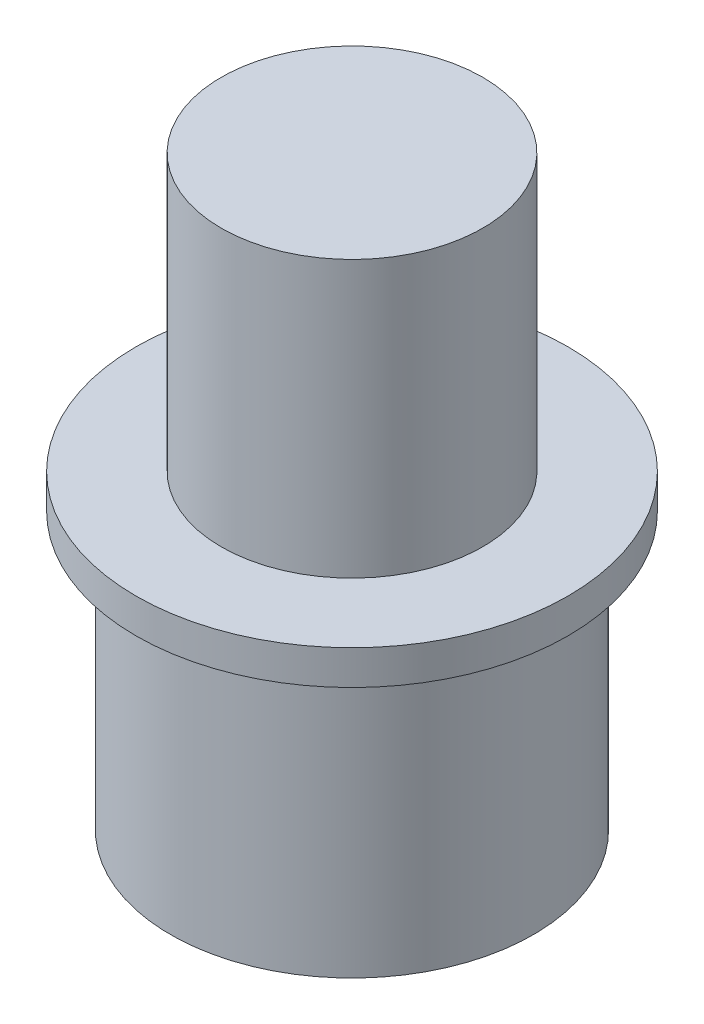
SolidWorks part; units mm, degrees
ref_plane "Front Plane" through (0, 0, 0) normal (0, 0, 1) x (1, 0, 0)
ref_plane "Top Plane" through (0, 0, 0) normal (0, 1, 0) x (1, 0, 0)
ref_plane "Right Plane" through (0, 0, 0) normal (1, 0, 0) x (0, 0, -1)
sketch "Sketch2" plane through (0, 0, 0) normal (0, 0, 1) x (1, 0, 0)
  line L2 (0, 0) -> (6.6802, 0)
  line L6 (0.1487, 0) -> (4.7625, 0)
  line L7 (6.6802, 0) -> (6.6802, 10.16)
  line L8 (6.6802, 10.16) -> (7.9502, 10.16)
  line L13 (7.9502, 10.16) -> (7.9502, 11.43)
  line L16 (4.8133, 11.43) -> (4.8133, 21.59)
  line L17 (4.8133, 21.59) -> (0, 21.59)
  line L18 (0, 0) -> (0, 21.59)
  line L19 (4.8133, 11.43) -> (7.9502, 11.43)
  line L21 (0, 0) -> (3.175, 0)
  line L22 (0, 0) -> (0, 8.89)
  line L23 (0, 8.89) -> (3.175, 8.89)
  line L24 (3.175, 0) -> (3.175, 8.89)
  dimension "D1" = 3.1369
  dimension "D2" = 6.6802
  dimension "D3" = 1.27
  dimension "D4" = 1.27
  dimension "D5" = 10.16
  dimension "D6" = 10.16
  dimension "D7" = 8.89
  dimension "D8" = 3.175
revolve "Revolve2" add sketch "Sketch2" angle 360 about L18
